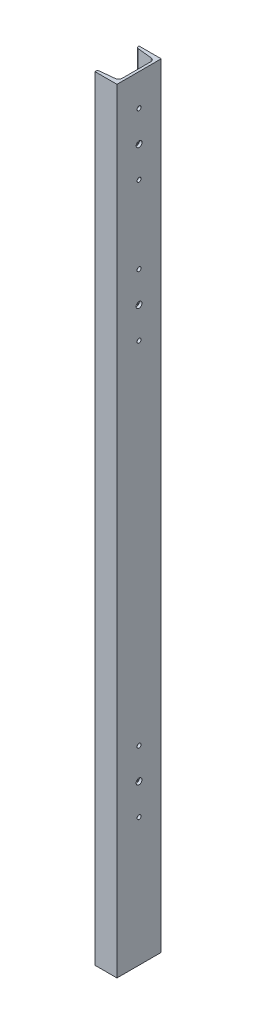
SolidWorks part; units mm, degrees
ref_plane "Płaszczyzna przednia" through (0, 0, 0) normal (0, 0, 1) x (1, 0, 0)
ref_plane "Płaszczyzna górna" through (0, 0, 0) normal (0, 1, 0) x (1, 0, 0)
ref_plane "Płaszczyzna prawa" through (0, 0, 0) normal (1, 0, 0) x (0, 0, -1)
sketch "Szkic1" plane through (0, 0, 0) normal (0, 0, 1) x (1, 0, 0)
  line L0 (0, 0) -> (0, 1750)
  dimension "D1" = 1750
other "Ceownik c 100 X 10(1)"
ref_plane "Płaszczyzna1" through (0, 0, 0) normal (0, 1, 0) x (-1, 0, 0)
sketch "Sketch1" plane through (0, 0, 0) normal (0, 1, 0) x (-1, 0, 0)
  line L0 (50, 100) -> (0, 100)
  line L1 (50, 0) -> (0, 0)
  line L2 (0, 100) -> (0, 0)
  line L6 (50, 100) -> (50, 98.3701)
  line L7 (50, 0) -> (50, 1.6299)
  line L12 (5.9, 82.48) -> (5.9, 17.52)
  line L17 (13.0638, 90.4362) -> (45.9704, 93.8948)
  line L18 (13.0638, 9.5638) -> (45.9704, 6.1052)
  arc A0 (45.9704, 93.8948) -> (50, 98.3701) centre (45.5, 98.3701) ccw
  arc A1 (45.9704, 6.1052) -> (50, 1.6299) centre (45.5, 1.6299) cw
  arc A9 (5.9, 17.52) -> (13.0638, 9.5638) centre (13.9, 17.52) ccw
  arc A10 (5.9, 82.48) -> (13.0638, 90.4362) centre (13.9, 82.48) cw
  point P8 (0, 50)
  point P9 (5.9, 50)
  point P10 (25, 100)
  point P11 (25, 0)
  point P12 (50, 5.6817)
  point P13 (50, 94.3183)
  point P14 (0, 0)
  dimension "D4" = 4.5
  dimension "RI" = 8
  dimension "D2" = 6
  dimension "D3" = 17.52
  dimension "Depth" = 100
  dimension "BF" = 50
  dimension "TW" = 5.9
  dimension "d1" = 64.96
sketch "Szkic3" plane through (0, 0, 0) normal (1, 0, 0) x (0, 0, -1)
  line L0 (0, 1750) -> (0, 0) construction
  line L1 (-100, 0) -> (0, 0) construction
  point P0 (-50, 360)
  point P1 (-50, 1608)
  point P2 (-50, 1293)
  dimension "D1" = 50
  dimension "D2" = 360
  dimension "D3" = 1293
  dimension "D4" = 1608
hole_wizard "Otwór Ø13.2 (13.2)1" positions "Szkic 3D1" profile "Szkic4" hole size "Ø13.2" standard "Ansi Metric"
sketch3d "Szkic 3D1"
  point P0 (0, 1608, 50)
  point P3 (0, 1293, 50)
  point P6 (0, 360, 50)
sketch "Szkic4" plane through (0, 1608, 50) normal (0, 1, 0) x (0, 0, -1)
  line L0 (0, 0) -> (0, 55)
  line L1 (0, 55) -> (6.6, 51.0343)
  line L2 (6.6, 51.0343) -> (6.6, 0)
  line L5 (6.6, 0) -> (0, 0)
  line L10 (0, 55) -> (-6.6, 51.0343) construction
  line L11 (0, -6.35) -> (0, 107.95) construction
  dimension "Średnica otworu" = 13.2
  dimension "Głębokość otworu" = 55
  dimension "Kąt wiertła" = 118
sketch "Szkic5" plane through (0, 0, 0) normal (1, 0, 0) x (0, 0, -1)
  point P0 (-50, 1678)
  point P1 (-50, 1538)
  point P2 (-50, 1363)
  point P3 (-50, 1223)
  point P4 (-50, 290)
  point P5 (-50, 430)
  dimension "D1" = 70
  dimension "D2" = 70
  dimension "D3" = 70
  dimension "D4" = 70
  dimension "D5" = 70
  dimension "D6" = 70
hole_wizard "Otwór Ø9.2 (9.2)1" positions "Szkic 3D2" profile "Szkic6" hole size "Ø9.2" standard "Ansi Metric"
sketch3d "Szkic 3D2"
  point P0 (0, 1538, 50)
  point P3 (0, 1678, 50)
  point P6 (0, 1363, 50)
  point P9 (0, 1223, 50)
  point P12 (0, 430, 50)
  point P15 (0, 290, 50)
sketch "Szkic6" plane through (0, 1538, 50) normal (0, 1, 0) x (0, 0, -1)
  line L0 (0, 0) -> (0, 55)
  line L1 (0, 55) -> (4.6, 52.236)
  line L2 (4.6, 52.236) -> (4.6, 0)
  line L5 (4.6, 0) -> (0, 0)
  line L10 (0, 55) -> (-4.6, 52.236) construction
  line L11 (0, -6.35) -> (0, 107.95) construction
  dimension "Średnica otworu" = 9.2
  dimension "Głębokość otworu" = 55
  dimension "Kąt wiertła" = 118
